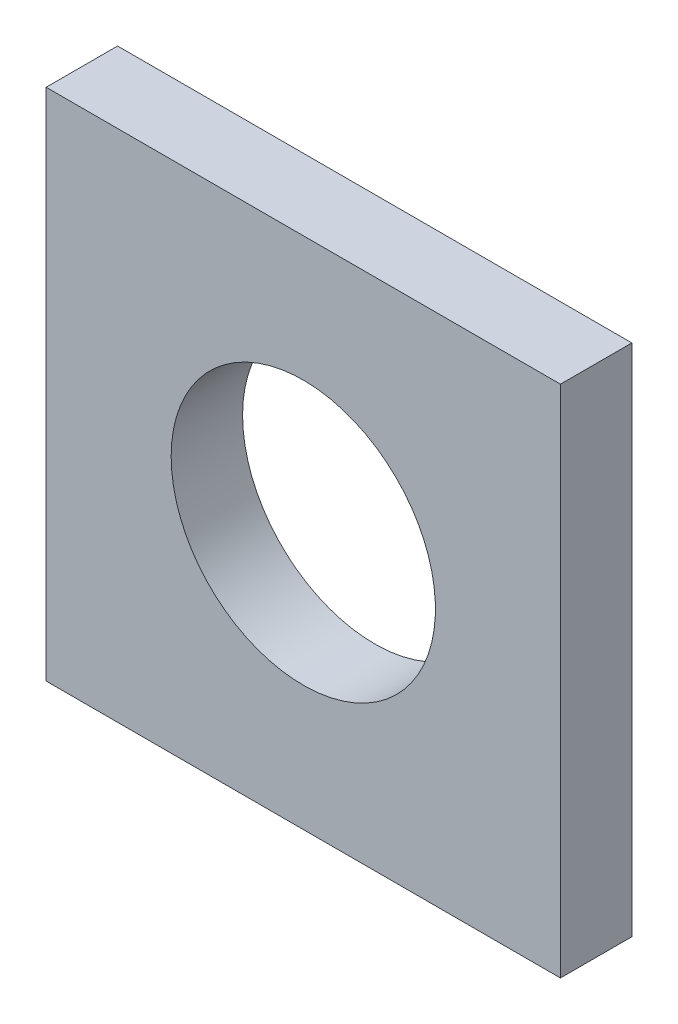
SolidWorks part; units mm, degrees
ref_plane "정면" through (0, 0, 0) normal (0, 0, 1) x (1, 0, 0)
ref_plane "윗면" through (0, 0, 0) normal (0, 1, 0) x (1, 0, 0)
ref_plane "우측면" through (0, 0, 0) normal (1, 0, 0) x (0, 0, -1)
sketch "스케치1" plane through (0, 0, 0) normal (0, 0, 1) x (1, 0, 0)
  line L0 (-0.1541, -15.7576) -> (69.1581, -15.7576) construction
  line L1 (17.8459, 15.2791) -> (17.8459, -49.4231) construction
  line L5 (-0.1541, 2.2424) -> (35.8459, 2.2424)
  line L6 (-0.1541, 2.2424) -> (-0.1541, -33.7576)
  line L7 (-0.1541, -33.7576) -> (35.8459, -33.7576)
  line L8 (35.8459, 2.2424) -> (35.8459, -33.7576)
  circle A0 centre (2.5959, -0.5076) radius 2.25
  circle A1 centre (17.8459, -0.5076) radius 2.25
  circle A2 centre (33.0959, -0.5076) radius 2.25
  circle A3 centre (33.0959, -15.7576) radius 2.25
  circle A4 centre (33.0959, -31.0076) radius 2.25
  circle A5 centre (17.8459, -31.0076) radius 2.25
  circle A6 centre (2.5959, -31.0076) radius 2.25
  circle A7 centre (2.5959, -15.7576) radius 2.25
  dimension "D3" = 36
  dimension "D1" = 4.5
  dimension "D2" = 4.5
  dimension "D5" = 4.5
  dimension "D6" = 4.5
  dimension "D7" = 4.5
  dimension "D8" = 4.5
  dimension "D9" = 4.5
  dimension "D10" = 4.5
  dimension "D4" = 36
  dimension "D11" = 15.25
  dimension "D12" = 15.25
  dimension "D13" = 15.25
  dimension "D14" = 15.25
  dimension "D15" = 15.25
  dimension "D16" = 18
  dimension "D17" = 15.25
  dimension "D18" = 15.25
  dimension "D19" = 15.25
  dimension "D20" = 15.25
  dimension "D21" = 15.25
  dimension "D22" = 15.25
  dimension "D23" = 15.25
  dimension "D24" = 15.25
  dimension "D25" = 15.25
  dimension "D26" = 15.25
  dimension "D27" = 15.25
extrude "보스-돌출1" add sketch "스케치1" along normal blind 3
sketch "스케치2" plane through (0, 0, 3) normal (0, 0, 1) x (1, 0, 0)
  line L1 (-0.1541, 2.2424) -> (35.8459, 2.2424)
  line L2 (-0.1541, 2.2424) -> (-0.1541, -33.7576)
  line L3 (-0.1541, -33.7576) -> (35.8459, -33.7576)
  line L4 (35.8459, 2.2424) -> (35.8459, -33.7576)
extrude "보스-돌출2" add sketch "스케치2" along normal blind 2
sketch "스케치4" plane through (0, 0, 0) normal (0, 0, -1) x (-1, 0, 0)
  line L0 (-35.8459, -33.7576) -> (-35.8459, 2.2424) construction
  line L2 (-35.8459, 2.2424) -> (0.1541, 2.2424) construction
  circle A0 centre (-17.8459, -15.7576) radius 9.25
  dimension "D1" = 18
  dimension "D3" = 18.5
  dimension "D2" = 18
extrude "컷-돌출1" cut sketch "스케치4" against normal through all
